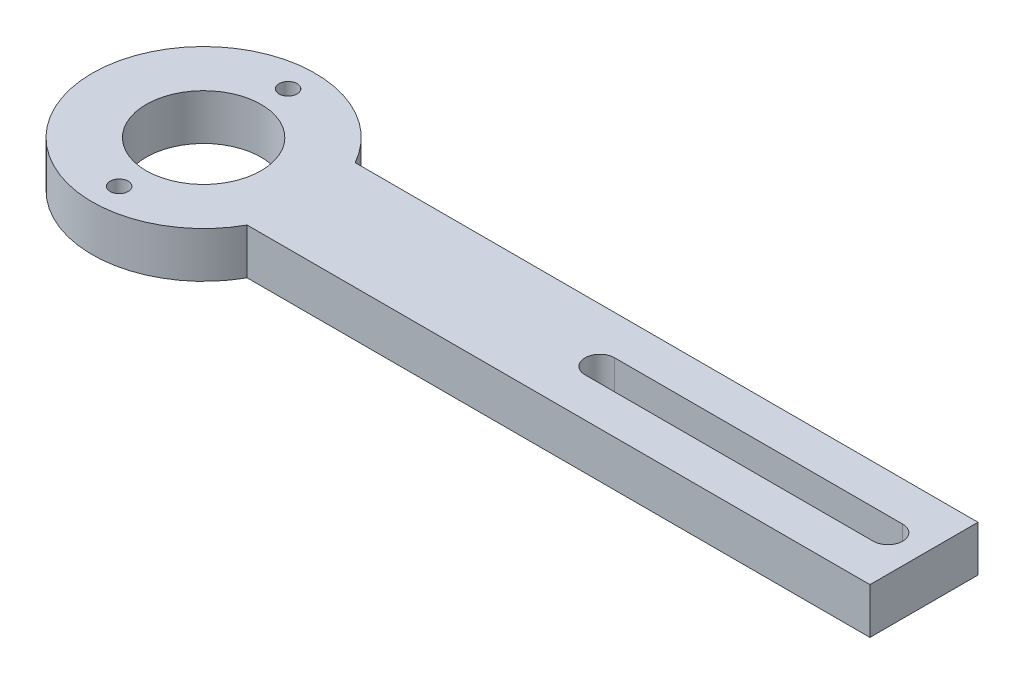
SolidWorks part; units mm, degrees
ref_plane "Front Plane" through (0, 0, 0) normal (0, 0, 1) x (1, 0, 0)
ref_plane "Top Plane" through (0, 0, 0) normal (0, 1, 0) x (1, 0, 0)
ref_plane "Right Plane" through (0, 0, 0) normal (1, 0, 0) x (0, 0, -1)
sketch "Sketch1" plane through (0, 0, 0) normal (0, 1, 0) x (1, 0, 0)
  line L0 (0, 0) -> (100, 0) construction
  line L1 (13.5361, 7.5) -> (100, 7.5)
  line L2 (100, 7.5) -> (100, -7.5)
  line L3 (100, -7.5) -> (13.5361, -7.5)
  line L4 (55, 0) -> (95, 0) construction
  line L5 (55, 2.05) -> (95, 2.05)
  line L6 (55, -2.05) -> (95, -2.05)
  arc A0 (13.5361, 7.5) -> (13.5361, -7.5) centre (0, 0) ccw
  circle A1 centre (0, 0) radius 7.975
  arc A2 (13.5361, -7.5) -> (13.5361, 7.5) centre (0, 0) ccw construction
  arc A3 (55, 2.05) -> (55, -2.05) centre (55, 0) ccw
  arc A4 (95, -2.05) -> (95, 2.05) centre (95, 0) ccw
  circle A5 centre (0, 0) radius 11.725 construction
  circle A6 centre (0, -11.725) radius 1.25
  circle A7 centre (0, 11.725) radius 1.25
  point P11 (75, 0)
  dimension "D1" = 15.95
  dimension "D2" = 30.95
  dimension "D5" = 4.1
  dimension "D8" = 7.5
  dimension "D9" = 23.45
  dimension "D10" = 2.5
  dimension "D3" = 15
  dimension "D4" = 100
  dimension "D6" = 40
  dimension "D7" = 5
extrude "Boss-Extrude1" add sketch "Sketch1" along normal blind 6.35
